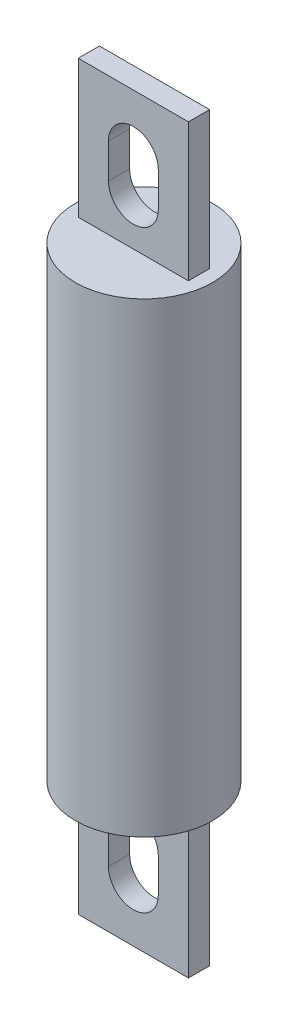
SolidWorks part; units mm, degrees
ref_plane "X-Y Datum" through (0, 0, 0) normal (0, 0, 1) x (1, 0, 0)
ref_plane "X-Z Datum" through (0, 0, 0) normal (0, 1, 0) x (1, 0, 0)
ref_plane "Y-Z Datum" through (0, 0, 0) normal (1, 0, 0) x (0, 0, -1)
sketch "Sketch1" plane through (0, 0, 0) normal (0, 1, 0) x (1, 0, 0)
  circle A0 centre (0, 0) radius 10.287
  dimension "D1" = 20.574
extrude "Boss-Extrude1" add sketch "Sketch1" along normal blind 69.85
sketch "Sketch2" plane through (0, 69.85, 0) normal (0, 1, 0) x (1, 0, 0)
  line L1 (-8.255, -1.5875) -> (8.255, -1.5875)
  line L2 (-8.255, -1.5875) -> (-8.255, 1.5875)
  line L3 (-8.255, 1.5875) -> (8.255, 1.5875)
  line L4 (8.255, -1.5875) -> (8.255, 1.5875)
  line L5 (-8.255, -1.5875) -> (8.255, 1.5875) construction
  line L6 (-8.255, 1.5875) -> (8.255, -1.5875) construction
  point P0 (0, 0)
  dimension "D1" = 3.175
extrude "Boss-Extrude2" add sketch "Sketch2" along normal blind 20.6375
ref_plane "Plane1" through (0, 34.925, 0) normal (0, 1, 0) x (1, 0, 0)
sketch "Sketch3" plane through (0, 0, 1.5875) normal (0, 0, 1) x (1, 0, 0)
  line L1 (11.3157, 34.925) -> (-11.3157, 34.925) construction
  line L2 (0, 34.925) -> (0, 82.0166) construction
  line L3 (0, 82.0166) -> (0, 76.8096) construction
  line L4 (3.7338, 82.0166) -> (3.7338, 76.8096)
  line L5 (-3.7338, 82.0166) -> (-3.7338, 76.8096)
  arc A0 (3.7338, 82.0166) -> (-3.7338, 82.0166) centre (0, 82.0166) ccw
  arc A1 (-3.7338, 76.8096) -> (3.7338, 76.8096) centre (0, 76.8096) ccw
  point P5 (0, 79.4131)
  dimension "D1" = 47.0916
  dimension "D2" = 5.207
extrude "Cut-Extrude1" cut sketch "Sketch3" against normal through all
mirror "Mirror2" about plane through (0, 34.925, 0) normal (0, 1, 0) of "Cut-Extrude1", "Boss-Extrude2"
sketch "Sketch4" plane through (0, 0, 1.5875) normal (0, 0, 1) x (1, 0, 0)
  line L0 (3.7338, -9.5631) -> (-3.7338, -9.5631)
  line L1 (3.7338, -6.9596) -> (3.7338, -12.1666) construction
  line L2 (-3.7338, -12.1666) -> (-3.7338, -6.9596) construction
  circle A0 centre (0, -9.5631) radius 2.2913
  point P6 (0, -9.5631)
